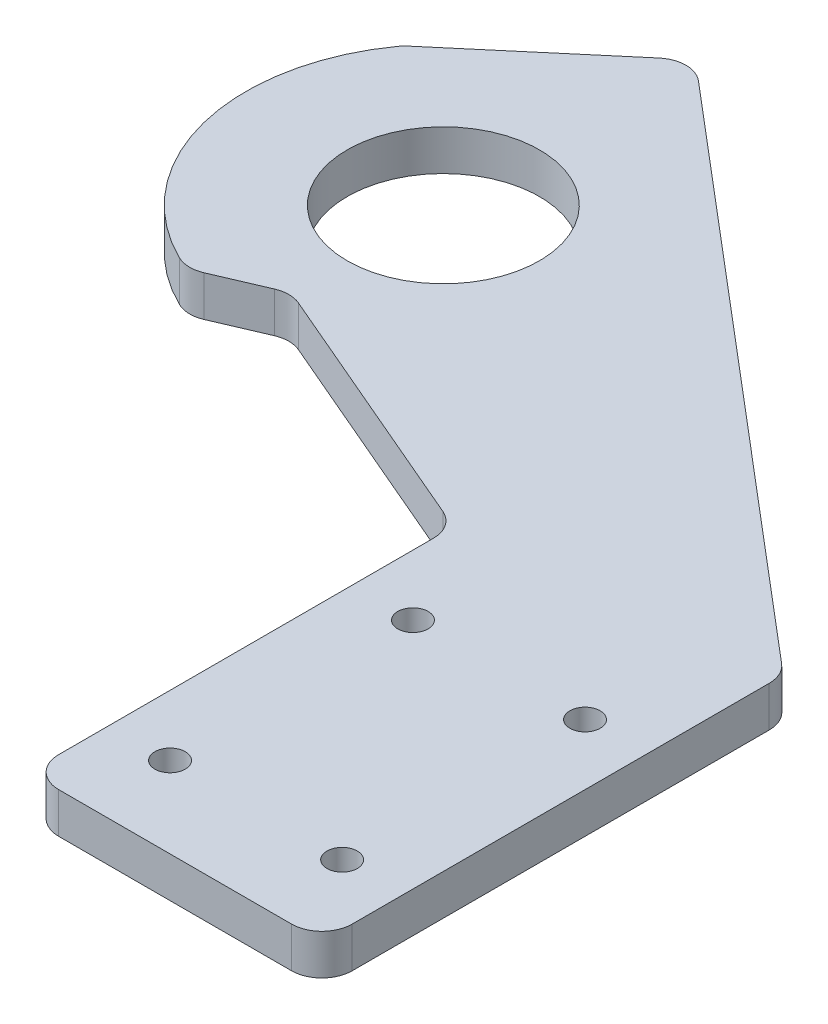
SolidWorks part; units mm, degrees
ref_plane "前视基准面" through (0, 0, 0) normal (0, 0, 1) x (1, 0, 0)
ref_plane "上视基准面" through (0, 0, 0) normal (0, 1, 0) x (1, 0, 0)
ref_plane "右视基准面" through (0, 0, 0) normal (1, 0, 0) x (0, 0, -1)
other "Configuration Table"
sketch "草图2" plane through (0, 0, 0) normal (0, 1, 0) x (1, 0, 0)
  line L0 (0, 0) -> (0, 60)
  line L1 (0, 60) -> (40, 93.9081)
  line L2 (40, 93.9081) -> (80, 60)
  line L3 (80, 60) -> (80, 0)
  line L4 (80, 0) -> (68, 0)
  line L5 (68, 0) -> (68, 42)
  line L6 (68, 42) -> (12, 42) construction
  line L7 (12, 42) -> (12, 0)
  line L8 (12, 0) -> (0, 0)
  line L9 (12, 42) -> (40, 54)
  line L10 (40, 54) -> (68, 42)
  line L11 (40, 93.9081) -> (40, 54) construction
  circle A0 centre (6, 32) radius 1.5
  circle A1 centre (6, 8) radius 1.5
  circle A2 centre (40, 69) radius 9.5
  circle A3 centre (74, 8) radius 1.5
  circle A4 centre (74, 32) radius 1.5
  dimension "D5" = 3
  dimension "D6" = 8
  dimension "D7" = 24
  dimension "D8" = 6
  dimension "D9" = 19
  dimension "D10" = 27
  dimension "D11" = 19
  dimension "D1" = 80
  dimension "D2" = 12
  dimension "D3" = 12
  dimension "D4" = 60
  dimension "D12" = 12
  dimension "D13" = 10
extrude "凸台-拉伸1" add sketch "草图2" along normal blind 4
sketch "草图4" plane through (0, 4, 0) normal (0, 1, 0) x (1, 0, 0)
  line L20 (0, 60) -> (0, 0)
  line L21 (0, 0) -> (12, 0)
  line L22 (12, 0) -> (12, 42)
  line L23 (12, 42) -> (40, 54)
  line L24 (40, 54) -> (68, 42)
  line L25 (68, 42) -> (68, 0)
  line L26 (68, 0) -> (80, 0)
  line L27 (80, 0) -> (80, 60)
  line L28 (80, 60) -> (40, 93.9081)
  line L29 (40, 93.9081) -> (0, 60)
  line L30 (0, 60) -> (0, 0)
  line L31 (0, 0) -> (12, 0)
  line L32 (12, 0) -> (12, 42)
  line L33 (12, 42) -> (40, 54)
  line L34 (40, 54) -> (68, 42)
  line L35 (68, 42) -> (68, 0)
  line L36 (68, 0) -> (80, 0)
  line L37 (80, 0) -> (80, 60)
  line L38 (80, 60) -> (40, 93.9081)
  line L39 (40, 93.9081) -> (0, 60)
  circle A2 centre (40, 69) radius 9.5
  circle A3 centre (40, 69) radius 9.5
  arc A13 (24.3672, 80.6562) -> (32.756, 50.8954) centre (40, 69) ccw
  dimension "D3" = 19.5
  dimension "D1" = 0
  dimension "D2" = 0
extrude "切除-拉伸1" cut sketch "草图4" against normal through all
sketch "草图6" plane through (0, 4, 0) normal (0, 1, 0) x (1, 0, 0)
  line L0 (68, 0) -> (80, 0) construction
  line L1 (80, 60) -> (97, 60) construction
  line L2 (80, 60) -> (80, 0)
  line L3 (80, 0) -> (97, 0)
  line L4 (97, 60) -> (97, 0)
  line L6 (80, 60) -> (97, 45.589)
  line L9 (80, 60) -> (40, 93.9081) construction
  line L10 (74, 32) -> (91, 32) construction
  circle A1 centre (40, 69) radius 9.5 construction
  circle A2 centre (40, 69) radius 9.5
  circle A4 centre (74, 8) radius 1.5 construction
  circle A5 centre (74, 32) radius 1.5 construction
  circle A6 centre (74, 8) radius 1.5
  circle A7 centre (74, 32) radius 1.5
  circle A8 centre (91, 32) radius 1.5
  circle A9 centre (91, 8) radius 1.5
  point P20 (88.7788, 32)
  line M13 (80, 0) -> (80, 60)
  dimension "D1" = 17
  dimension "D3" = 17
  dimension "D2" = 2
extrude "凸台-拉伸2" add sketch "草图6" against normal up to surface (4 mm away) contours L6 L3 L4 A9 A8 M13 up to face at (53.2241, 0, -47.4242)
fillet "圆角1" radius 3 8 edges at (32.756, 2, -50.8954) (40, 2, -54) (68, 2, -42) (68, 2, 0) (97, 2, 0) (40, 2, -93.9081) (24.3672, 2, -80.6562) (97, 2, -45.589)
